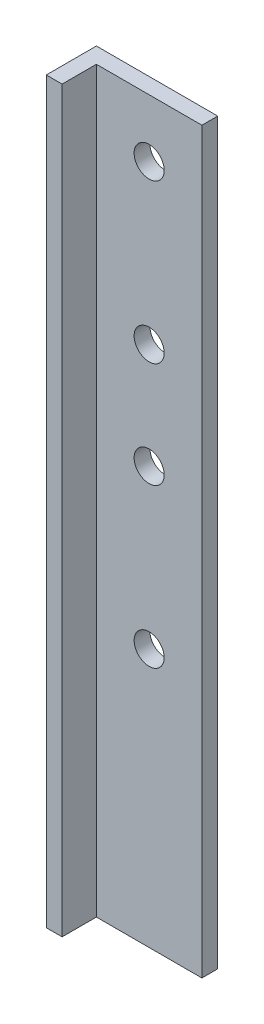
SolidWorks part; units mm, degrees
ref_plane "Front Plane" through (0, 0, 0) normal (0, 0, 1) x (1, 0, 0)
ref_plane "Top Plane" through (0, 0, 0) normal (0, 1, 0) x (1, 0, 0)
ref_plane "Right Plane" through (0, 0, 0) normal (1, 0, 0) x (0, 0, -1)
sketch "Sketch1" plane through (0, 0, 0) normal (0, 0, 1) x (1, 0, 0)
  line L1 (-11.5, -70) -> (11.5, -70)
  line L2 (-11.5, -70) -> (-11.5, 70)
  line L3 (-11.5, 70) -> (11.5, 70)
  line L4 (11.5, -70) -> (11.5, 70)
  line L5 (-11.5, -70) -> (11.5, 70) construction
  line L6 (-11.5, 70) -> (11.5, -70) construction
  point P0 (0, 0)
  dimension "D1" = 23
  dimension "D2" = 140
extrude "Boss-Extrude1" add sketch "Sketch1" against normal blind 3
sketch "Sketch4" plane through (0, 0, 0) normal (0, 0, 1) x (1, 0, 0)
  line L1 (-11.5, -70) -> (11.5, -70) construction
  line L2 (-11.5, 70) -> (-8.5, 70)
  line L3 (-11.5, 70) -> (-11.5, -70)
  line L4 (-11.5, -70) -> (-8.5, -70)
  line L5 (-8.5, 70) -> (-8.5, -70)
  dimension "D1" = 3
extrude "Boss-Extrude3" add sketch "Sketch4" along normal blind 6.5
sketch "Sketch3" plane through (0, 0, 0) normal (0, 0, 1) x (1, 0, 0)
  line L0 (1.5, 70) -> (1.5, -70) construction
  line L1 (11.5, 70) -> (-8.5, 70) construction
  line L2 (-8.5, -70) -> (11.5, -70) construction
  line L4 (11.5, -70) -> (11.5, 70) construction
  line L5 (11.5, 70) -> (-11.5, 70) construction
  circle A0 centre (1.5, 59) radius 2.85
  circle A1 centre (1.5, 29) radius 2.85
  circle A2 centre (1.5, 9) radius 2.85
  circle A3 centre (1.5, -21) radius 2.85
  dimension "D2" = 5.7
  dimension "D3" = 30
  dimension "D1" = 10
  dimension "D4" = 20
  dimension "D5" = 30
  dimension "D6" = 11
extrude "Cut-Extrude5" cut sketch "Sketch3" against normal blind 8.5
